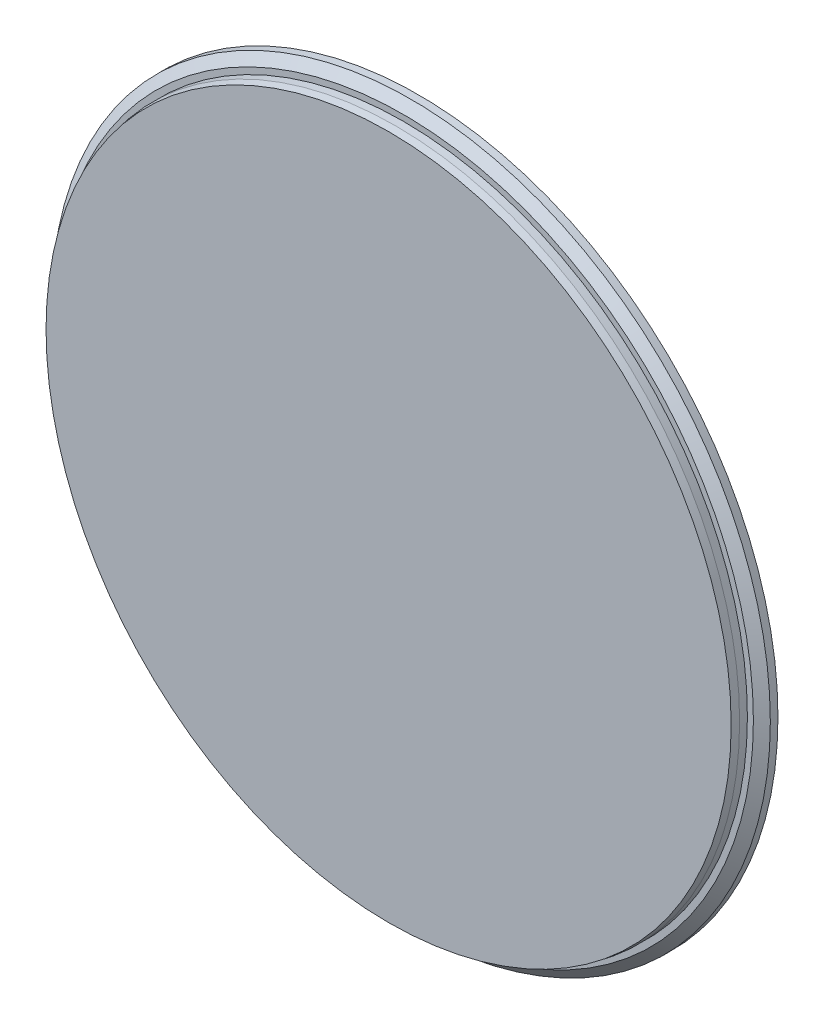
SolidWorks part; units mm, degrees
ref_plane "Front Plane" through (0, 0, 0) normal (0, 0, 1) x (1, 0, 0)
ref_plane "Top Plane" through (0, 0, 0) normal (0, 1, 0) x (1, 0, 0)
ref_plane "Right Plane" through (0, 0, 0) normal (1, 0, 0) x (0, 0, -1)
sketch "Sketch1" plane through (0, 0, 0) normal (1, 0, 0) x (0, 0, -1)
  line L0 (-7.9892, 0) -> (21.2344, 0) construction
  line L1 (0, 0) -> (0, 36.3146)
  line L2 (0.762, 36.449) -> (1.5875, 36.449)
  line L3 (1.5875, 36.449) -> (1.5875, 37.084)
  line L4 (1.5875, 37.084) -> (2.3671, 38.1)
  line L5 (2.3671, 38.1) -> (3.175, 38.1)
  line L6 (3.175, 38.1) -> (3.175, 0)
  line L7 (3.175, 0) -> (0, 0)
  line L8 (0.762, 36.449) -> (0, 36.3146)
  dimension "D1" = 76.2
  dimension "D2" = 1.5875
  dimension "D3" = 1.5875
  dimension "D4" = 72.898
  dimension "D5" = 37.5
  dimension "D6" = 1.016
  dimension "D7" = 10
  dimension "D8" = 0.762
revolve "Revolve1" add sketch "Sketch1" angle 360 about L0
